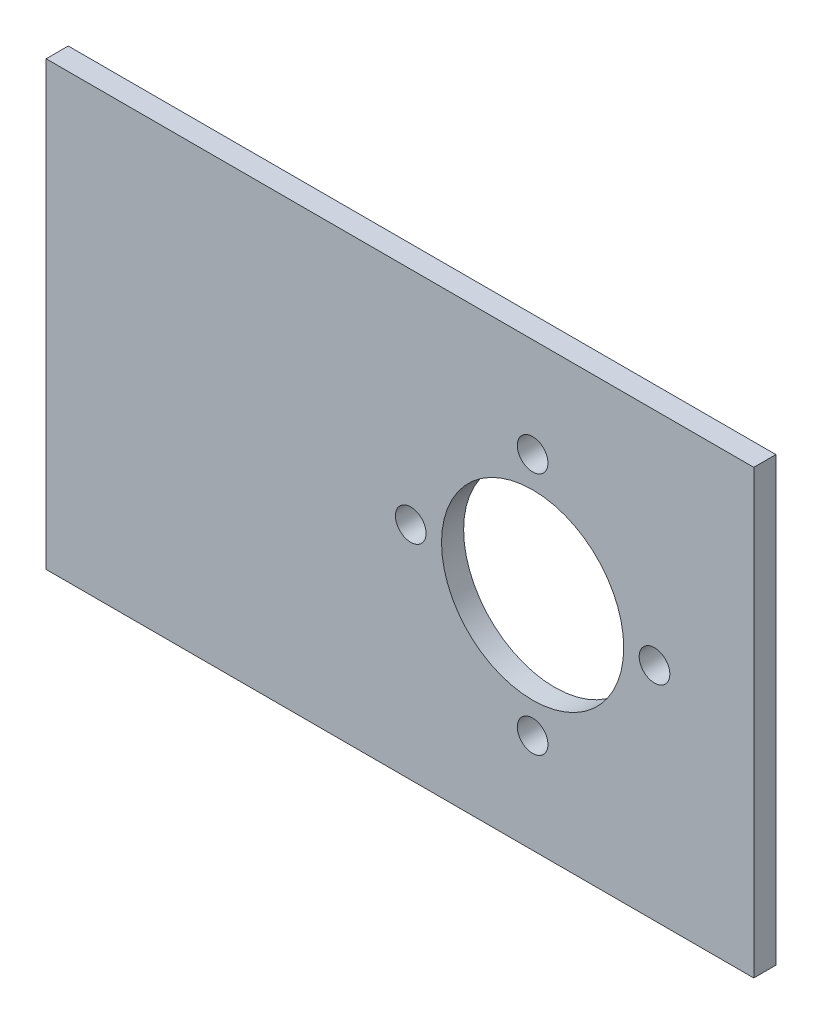
SolidWorks part; units mm, degrees
ref_plane "Front Plane" through (0, 0, 0) normal (0, 0, 1) x (1, 0, 0)
ref_plane "Top Plane" through (0, 0, 0) normal (0, 1, 0) x (1, 0, 0)
ref_plane "Right Plane" through (0, 0, 0) normal (1, 0, 0) x (0, 0, -1)
sketch "Sketch1" plane through (0, 0, 0) normal (0, 0, 1) x (1, 0, 0)
  line L1 (-69.85, 31.75) -> (31.75, 31.75)
  line L2 (-69.85, 31.75) -> (-69.85, -31.75)
  line L3 (-69.85, -31.75) -> (31.75, -31.75)
  line L4 (31.75, 31.75) -> (31.75, -31.75)
  arc A0 (-2.1956, 17.3623) -> (-17.3623, 2.1956) centre (0, 0) ccw
  circle A1 centre (0, 17.5006) radius 2.2
  circle A2 centre (17.5006, 0) radius 2.2
  circle A3 centre (0, -17.5006) radius 2.2
  circle A4 centre (-17.5006, 0) radius 2.2
  circle A5 centre (0, 0) radius 13.081
  circle A6 centre (0, 0) radius 22.5044
  arc A7 (-17.3623, -2.1956) -> (-2.1956, -17.3623) centre (0, 0) ccw
  arc A8 (17.3623, 2.1956) -> (2.1956, 17.3623) centre (0, 0) ccw
  arc A9 (2.1956, -17.3623) -> (17.3623, -2.1956) centre (0, 0) ccw
  point P14 (0, 0)
  dimension "D1" = 35.0012
  dimension "D2" = 4.4
  dimension "D5" = 26.162
  dimension "D6" = 45.0088
  dimension "D4" = 0
  dimension "D7" = 31.75
  dimension "D8" = 31.75
  dimension "D9" = 31.75
  dimension "D10" = 69.85
  dimension "D3" = 4
extrude "Boss-Extrude1" add sketch "Sketch1" along normal blind 3.175
